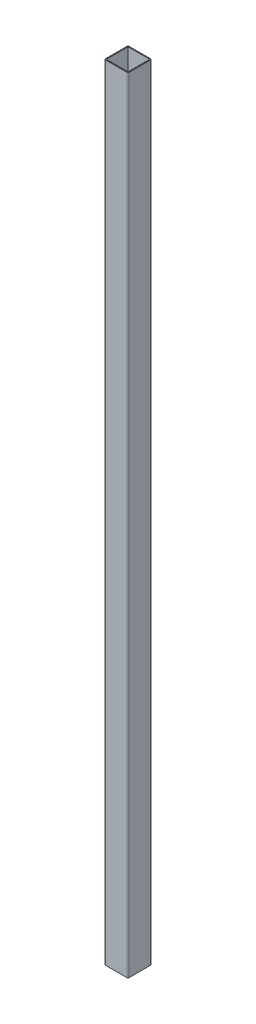
SolidWorks part; units mm, degrees
material "Простая углеродистая сталь"
ref_plane "Спереди" through (0, 0, 0) normal (0, 0, 1) x (1, 0, 0)
ref_plane "Сверху" through (0, 0, 0) normal (0, 1, 0) x (1, 0, 0)
ref_plane "Справа" through (0, 0, 0) normal (1, 0, 0) x (0, 0, -1)
sketch "Эскиз1" plane through (0, 0, 0) normal (0, 0, 1) x (1, 0, 0)
  line L0 (0, 0) -> (0, -5328)
  dimension "D1" = 5328
other "Квадратная труба гост 8639-82 150 X 150 X 7.0(1)"
ref_plane "Плоскость1" through (0, 0, 0) normal (0, -1, 0) x (1, 0, 0)
sketch "Sketch1" plane through (0, 0, 0) normal (0, -1, 0) x (1, 0, 0)
  line L0 (-73.999, -74) -> (73.999, -74)
  line L1 (-74, -73.999) -> (-74, 73.999)
  line L2 (73.999, 74) -> (-73.999, 74)
  line L3 (74, 73.999) -> (74, -73.999)
  line L4 (-73.999, -80) -> (73.999, -80)
  line L5 (-80, -73.999) -> (-80, 73.999)
  line L6 (73.999, 80) -> (-73.999, 80)
  line L7 (80, 73.999) -> (80, -73.999)
  arc A0 (80, 73.999) -> (73.999, 80) centre (73.999, 73.999) ccw
  arc A1 (73.999, -80) -> (80, -73.999) centre (73.999, -73.999) ccw
  arc A2 (-80, -73.999) -> (-73.999, -80) centre (-73.999, -73.999) ccw
  arc A3 (-73.999, 80) -> (-80, 73.999) centre (-73.999, 73.999) ccw
  arc A4 (-73.999, 74) -> (-74, 73.999) centre (-73.999, 73.999) ccw
  arc A5 (74, 73.999) -> (73.999, 74) centre (73.999, 73.999) ccw
  arc A6 (73.999, -74) -> (74, -73.999) centre (73.999, -73.999) ccw
  arc A7 (-74, -73.999) -> (-73.999, -74) centre (-73.999, -73.999) ccw
  point P0 (-80, 0)
  point P1 (80, 0)
  point P2 (0, 80)
  point P3 (0, -80)
  point P4 (0, 0)
  point P5 (-80, -80)
  point P6 (80, -80)
  point P7 (80, 80)
  point P8 (-80, 80)
  point P33 (0, 0)
  dimension "D1" = 6.001
  dimension "Thickness" = 6
  dimension "V_leg" = 160
sketch "Эскиз3" plane through (0, 0, 80) normal (0, 0, 1) x (1, 0, 0)
  line L0 (-80, 0) -> (80, -20)
  line L1 (80, -5328) -> (80, 0) construction
  line L2 (80, -20) -> (80, 0)
  line L3 (80, 0) -> (-80, 0)
  dimension "D1" = 20
extrude "Вырез-Вытянуть1" [suppressed] cut sketch "Эскиз3" against normal up to vertex
equation "\"D1@Sketch1\" = \"Thickness@Sketch1\"+0.001"
